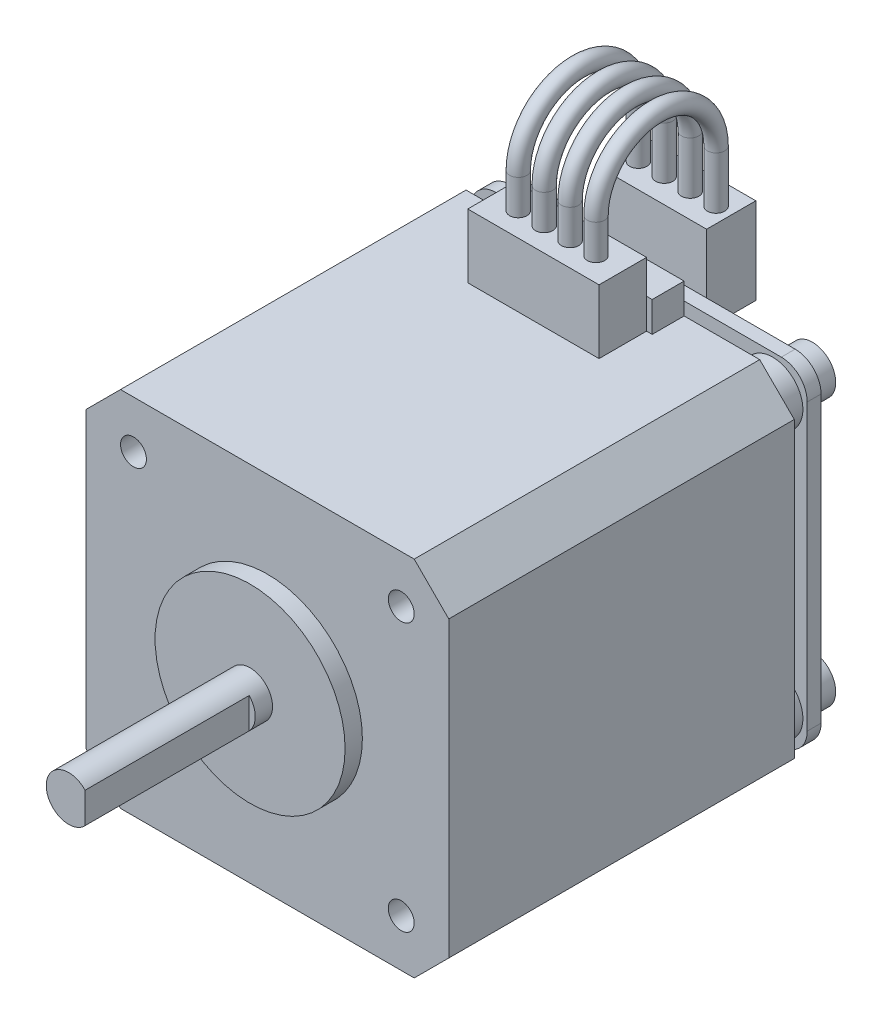
SolidWorks part; units mm, degrees
ref_plane "Front Plane" through (0, 0, 0) normal (0, 0, 1) x (1, 0, 0)
ref_plane "Top Plane" through (0, 0, 0) normal (0, 1, 0) x (1, 0, 0)
ref_plane "Right Plane" through (0, 0, 0) normal (1, 0, 0) x (0, 0, -1)
sketch "Sketch1" plane through (0, 0, 0) normal (0, 0, 1) x (1, 0, 0)
  circle A0 centre (0, 0) radius 11
  dimension "D1" = 22
extrude "Boss-Extrude1" add sketch "Sketch1" along normal blind 2
sketch "Sketch2" plane through (0, 0, 2) normal (0, 0, 1) x (1, 0, 0)
  circle A0 centre (0, 0) radius 2.6
  dimension "D1" = 5.2
extrude "Boss-Extrude2" add sketch "Sketch2" along normal blind 21
sketch "Sketch3" plane through (0, 0, 23) normal (0, 0, 1) x (1, 0, 0)
  line L0 (1.9, 1.7748) -> (1.9, -1.7748)
  circle A0 centre (0, 0) radius 2.6 construction
  arc A1 (1.9, -1.7748) -> (1.9, 1.7748) centre (0, 0) ccw
  circle A2 centre (0, 0) radius 2.6 construction
  dimension "D1" = 4.5
extrude "Cut-Extrude1" cut sketch "Sketch3" against normal blind 19
sketch "Sketch4" plane through (0, 0, 0) normal (0, 0, -1) x (-1, 0, 0)
  line L1 (-21, -21) -> (21, -21)
  line L2 (-21, -21) -> (-21, 21)
  line L3 (-21, 21) -> (21, 21)
  line L4 (21, -21) -> (21, 21)
  line L5 (-21, -21) -> (21, 21) construction
  line L6 (-21, 21) -> (21, -21) construction
  point P0 (0, 0)
  dimension "D1" = 42
extrude "Boss-Extrude3" add sketch "Sketch4" along normal blind 40
chamfer "Chamfer1" distance 4 angle 45 4 edges at (21, 21, -20) (-21, -21, -20) (-21, 21, -20) (21, -21, -20)
sketch "Sketch5" plane through (0, 0, -40) normal (0, 0, -1) x (-1, 0, 0)
  line L1 (-15.5, -15.5) -> (15.5, -15.5)
  line L2 (-15.5, -15.5) -> (-15.5, 15.5)
  line L3 (-15.5, 15.5) -> (15.5, 15.5)
  line L4 (15.5, -15.5) -> (15.5, 15.5)
  line L5 (-15.5, -15.5) -> (15.5, 15.5) construction
  line L6 (-15.5, 15.5) -> (15.5, -15.5) construction
  circle A0 centre (-15.5, 15.5) radius 1.5
  circle A1 centre (15.5, 15.5) radius 1.5
  circle A2 centre (15.5, -15.5) radius 1.5
  circle A3 centre (-15.5, -15.5) radius 1.5
  point P0 (0, 0)
  dimension "D2" = 3
  dimension "D1" = 31
extrude "Cut-Extrude2" cut sketch "Sketch5" against normal through all contours L3 A0 L2 | L2 A0 L3 | L4 A1 L3 | L3 A1 L4 | L1 A2 L4 | L4 A2 L1 | L2 A3 L1 | L1 A3 L2
sketch "Sketch6" plane through (0, 0, -40) normal (0, 0, -1) x (-1, 0, 0)
  circle A0 centre (-15.5, 15.5) radius 3.5
  circle A1 centre (15.5, 15.5) radius 3.5
  circle A2 centre (15.5, -15.5) radius 3.5
  circle A3 centre (-15.5, -15.5) radius 3.5
  dimension "D1" = 7
extrude "Boss-Extrude4" add sketch "Sketch6" along normal blind 3
sketch "Sketch7" plane through (0, 0, -43) normal (0, 0, -1) x (-1, 0, 0)
  line L1 (-19.5, -19.5) -> (19.5, -19.5)
  line L2 (-19.5, -19.5) -> (-19.5, 19.5)
  line L3 (-19.5, 19.5) -> (19.5, 19.5)
  line L4 (19.5, -19.5) -> (19.5, 19.5)
  line L5 (-19.5, -19.5) -> (19.5, 19.5) construction
  line L6 (-19.5, 19.5) -> (19.5, -19.5) construction
  point P0 (0, 0)
  dimension "D1" = 39
extrude "Boss-Extrude5" add sketch "Sketch7" along normal blind 1.6
fillet "Fillet1" radius 3 4 edges at (19.5, -19.5, -43.8) (-19.5, -19.5, -43.8) (-19.5, 19.5, -43.8) (19.5, 19.5, -43.8)
sketch "Sketch8" plane through (0, 0, -40) normal (0, 0, -1) x (-1, 0, 0)
  line L0 (17, 21) -> (-17, 21) construction
  line L1 (-8.25, 17.5) -> (8.25, 17.5)
  line L2 (-8.25, 17.5) -> (-8.25, 24.5)
  line L3 (-8.25, 24.5) -> (8.25, 24.5)
  line L4 (8.25, 17.5) -> (8.25, 24.5)
  line L5 (-8.25, 17.5) -> (8.25, 24.5) construction
  line L6 (-8.25, 24.5) -> (8.25, 17.5) construction
  point P0 (0, 21)
  dimension "D1" = 16.5
  dimension "D2" = 3.5
extrude "Boss-Extrude6" add sketch "Sketch8" against normal blind 3.7
sketch "Sketch9" plane through (0, 21, 0) normal (0, 1, 0) x (1, 0, 0)
  line L0 (0, 0) -> (0, 36.3) construction
  line L1 (8.25, 36.3) -> (-8.25, 36.3) construction
  line L2 (-8.25, 36.3) -> (8.25, 36.3) construction
  line L3 (-7.6, 36.3) -> (7.6, 36.3)
  line L4 (-7.6, 36.3) -> (-7.6, 30.8)
  line L5 (-7.6, 30.8) -> (7.6, 30.8)
  line L6 (7.6, 36.3) -> (7.6, 30.8)
  line L7 (-7.6, 36.3) -> (7.6, 30.8) construction
  line L8 (-7.6, 30.8) -> (7.6, 36.3) construction
  point P5 (0, 33.55)
  point P10 (7.6, 36.3)
  dimension "D1" = 5.5
  dimension "D2" = 15.2
extrude "Boss-Extrude7" add sketch "Sketch9" along normal blind 7.4
sketch "Sketch10" plane through (0, 0, -44.6) normal (0, 0, -1) x (-1, 0, 0)
  line L0 (0, 0) -> (0, 19.5) construction
  line L1 (16.5, 19.5) -> (-16.5, 19.5) construction
  line L2 (-7.6, 28.4) -> (7.6, 28.4) construction
  line L3 (-6.25, 16.4) -> (6.25, 16.4)
  line L4 (-6.25, 16.4) -> (-6.25, 26.4)
  line L5 (-6.25, 26.4) -> (6.25, 26.4)
  line L6 (6.25, 16.4) -> (6.25, 26.4)
  line L7 (-6.25, 16.4) -> (6.25, 26.4) construction
  line L8 (-6.25, 26.4) -> (6.25, 16.4) construction
  point P5 (0, 21.4)
  dimension "D1" = 10
  dimension "D2" = 12.5
  dimension "D3" = 2
extrude "Boss-Extrude8" add sketch "Sketch10" along normal blind 5.7
sketch "Sketch11" plane through (0, 26.4, 0) normal (0, 1, 0) x (1, 0, 0)
  line L0 (-6.25, 47.45) -> (6.25, 47.45) construction
  line L1 (-6.25, 50.3) -> (-6.25, 44.6) construction
  line L2 (6.25, 50.3) -> (6.25, 44.6) construction
  line L3 (-4.5, 47.45) -> (-4.5, 44.6) construction
  line L4 (-6.25, 44.6) -> (6.25, 44.6) construction
  line L5 (-1.5, 47.45) -> (-1.5, 44.6) construction
  line L6 (-6.25, 44.6) -> (6.25, 44.6) construction
  line L7 (1.5, 47.45) -> (1.5, 44.6) construction
  line L8 (4.5, 47.45) -> (4.5, 44.6) construction
  line L9 (-4.5, 46.025) -> (-1.5, 46.025) construction
  line L10 (-1.5, 46.025) -> (1.5, 46.025) construction
  line L11 (1.5, 46.025) -> (4.5, 46.025) construction
  line L12 (-6.25, 50.3) -> (-4.5, 47.45) construction
  line L13 (6.25, 50.3) -> (4.5, 47.45) construction
  circle A0 centre (-4.5, 47.45) radius 1
  circle A1 centre (-1.5, 47.45) radius 1
  circle A2 centre (1.5, 47.45) radius 1
  circle A3 centre (4.5, 47.45) radius 1
  point P29 (4.2453, 47.45)
  dimension "D1" = 2
  dimension "D2" = 9
sketch "Sketch12" plane through (0, 0, 0) normal (1, 0, 0) x (0, 0, -1)
  line L0 (33.55, 28.4) -> (33.55, 24.0981) construction
  line L1 (30.8, 28.4) -> (36.3, 28.4) construction
  line L2 (47.45, 26.4) -> (47.45, 22.93) construction
  line L3 (48.45, 26.4) -> (46.45, 26.4) construction
  line L4 (33.55, 28.4) -> (33.55, 32.45)
  line L5 (47.45, 32.45) -> (47.45, 26.4)
  arc A0 (33.55, 32.45) -> (47.45, 32.45) centre (40.5, 32.45) cw
  dimension "D1" = 11
sweep "Sweep1" add profiles "Sketch11" path "Sketch12"
sketch "Sketch13" plane through (0, 0, -44.6) normal (0, 0, -1) x (-1, 0, 0)
  circle A0 centre (-15.5, -15.5) radius 1.5 construction
  circle A1 centre (15.5, -15.5) radius 1.5 construction
  circle A2 centre (15.5, 15.5) radius 1.5 construction
  circle A3 centre (-15.5, 15.5) radius 1.5 construction
  circle A4 centre (-15.5, -15.5) radius 1.5 construction
  circle A5 centre (15.5, -15.5) radius 1.5 construction
  circle A6 centre (15.5, 15.5) radius 1.5 construction
  circle A7 centre (-15.5, 15.5) radius 1.5 construction
  circle A8 centre (-15.5, 15.5) radius 2.7
  circle A9 centre (15.5, 15.5) radius 2.7
  circle A10 centre (-15.5, -15.5) radius 2.7
  circle A11 centre (15.5, -15.5) radius 2.7
  dimension "D2" = 1.2
  dimension "D1" = 1.2
  dimension "D3" = 1.2
  dimension "D4" = 1.2
extrude "Boss-Extrude9" add sketch "Sketch13" along normal blind 3
sketch "Sketch14" plane through (0, 0, -44.6) normal (0, 0, -1) x (-1, 0, 0)
  line L1 (-6, -5) -> (6, -5)
  line L2 (-6, -5) -> (-6, 5)
  line L3 (-6, 5) -> (6, 5)
  line L4 (6, -5) -> (6, 5)
  line L5 (-6, -5) -> (6, 5) construction
  line L6 (-6, 5) -> (6, -5) construction
  point P0 (0, 0)
  dimension "D1" = 10
  dimension "D2" = 12
extrude "Boss-Extrude10" add sketch "Sketch14" along normal blind 2
sketch "Sketch15" plane through (0, 0, -44.6) normal (0, 0, -1) x (-1, 0, 0)
  line L0 (-19.5, -17.5) -> (19.5, -17.5) construction
  line L1 (-19.5, 16.5) -> (-19.5, -16.5) construction
  line L2 (19.5, -16.5) -> (19.5, 16.5) construction
  line L3 (0, -17.5) -> (0, 0) construction
  line L4 (-10.5, -19) -> (-5.5, -19)
  line L5 (-10.5, -19) -> (-10.5, -16)
  line L6 (-10.5, -16) -> (-5.5, -16)
  line L7 (-5.5, -19) -> (-5.5, -16)
  line L8 (-10.5, -19) -> (-5.5, -16) construction
  line L9 (-10.5, -16) -> (-5.5, -19) construction
  line L10 (-2.5, -19) -> (2.5, -19)
  line L11 (-2.5, -19) -> (-2.5, -16)
  line L12 (-2.5, -16) -> (2.5, -16)
  line L13 (2.5, -19) -> (2.5, -16)
  line L14 (-2.5, -19) -> (2.5, -16) construction
  line L15 (-2.5, -16) -> (2.5, -19) construction
  line L16 (5.5, -19) -> (10.5, -19)
  line L17 (5.5, -19) -> (5.5, -16)
  line L18 (5.5, -16) -> (10.5, -16)
  line L19 (10.5, -19) -> (10.5, -16)
  line L20 (5.5, -19) -> (10.5, -16) construction
  line L21 (5.5, -16) -> (10.5, -19) construction
  line L22 (0, 0) -> (-8, -17.5) construction
  line L23 (0, 0) -> (8, -17.5) construction
  line L24 (-17, -21) -> (17, -21) construction
  point P6 (-8, -17.5)
  point P11 (0, -17.5)
  point P16 (8, -17.5)
  dimension "D1" = 5
  dimension "D2" = 3
  dimension "D3" = 3.5
  dimension "D4" = 8
extrude "Boss-Extrude11" add sketch "Sketch15" along normal blind 4
sketch "Sketch16" plane through (0, 0, -44.6) normal (0, 0, -1) x (-1, 0, 0)
  line L0 (0, 0) -> (34.9064, 0) construction
  line L1 (21, -17) -> (21, 17) construction
  line L2 (16.8, -8.75) -> (24, -8.75)
  line L3 (16.8, -8.75) -> (16.8, 8.75)
  line L4 (16.8, 8.75) -> (24, 8.75)
  line L5 (24, -8.75) -> (24, 8.75)
  line L6 (16.8, -8.75) -> (24, 8.75) construction
  line L7 (16.8, 8.75) -> (24, -8.75) construction
  point P3 (20.4, 0)
  dimension "D1" = 7.2
  dimension "D2" = 17.5
  dimension "D3" = 3
extrude "Boss-Extrude12" add sketch "Sketch16" along normal up to surface (5.7 mm away) up to face at (0, 21.4, -50.3)
